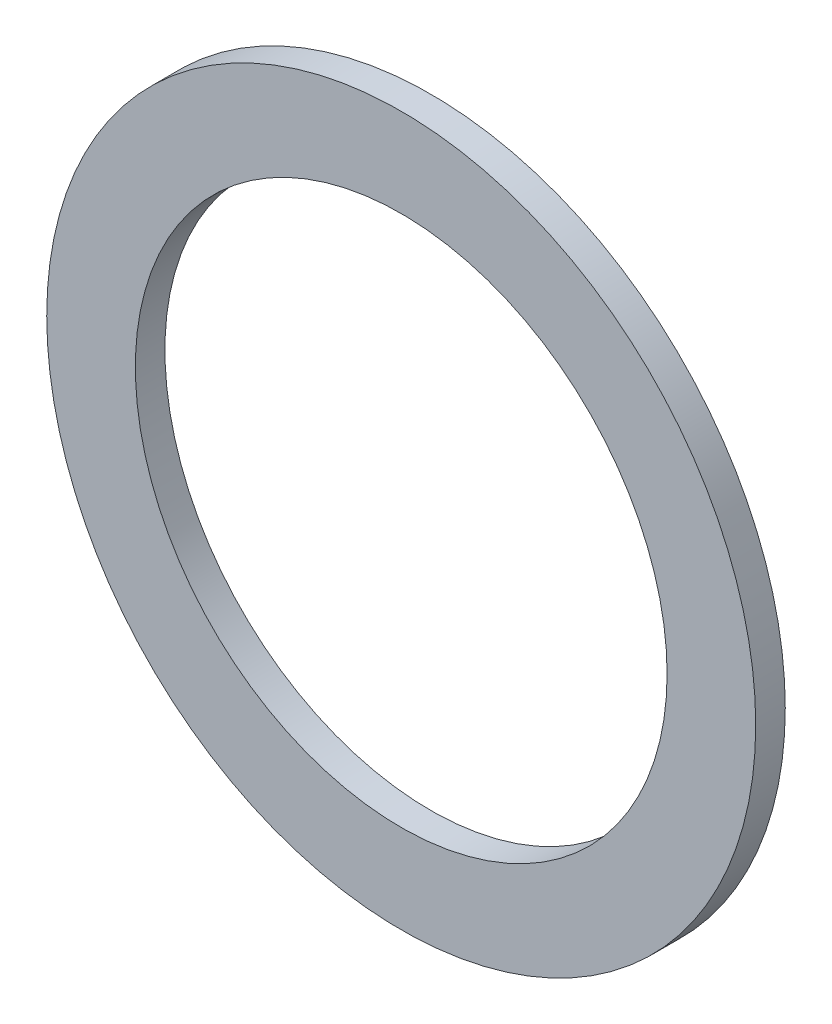
SolidWorks part; units mm, degrees
material "AISI 316 Stainless Steel Sheet (SS)"
ref_plane "Front Plane" through (0, 0, 0) normal (0, 0, 1) x (1, 0, 0)
ref_plane "Top Plane" through (0, 0, 0) normal (0, 1, 0) x (1, 0, 0)
ref_plane "Right Plane" through (0, 0, 0) normal (1, 0, 0) x (0, 0, -1)
sketch "Sketch1" plane through (0, 0, 0) normal (0, 0, 1) x (1, 0, 0)
  circle A0 centre (0, 0) radius 12
  circle A1 centre (0, 0) radius 9
  dimension "D1" = 24
  dimension "D2" = 18
extrude "Boss-Extrude1" add sketch "Sketch1" along normal blind 1
